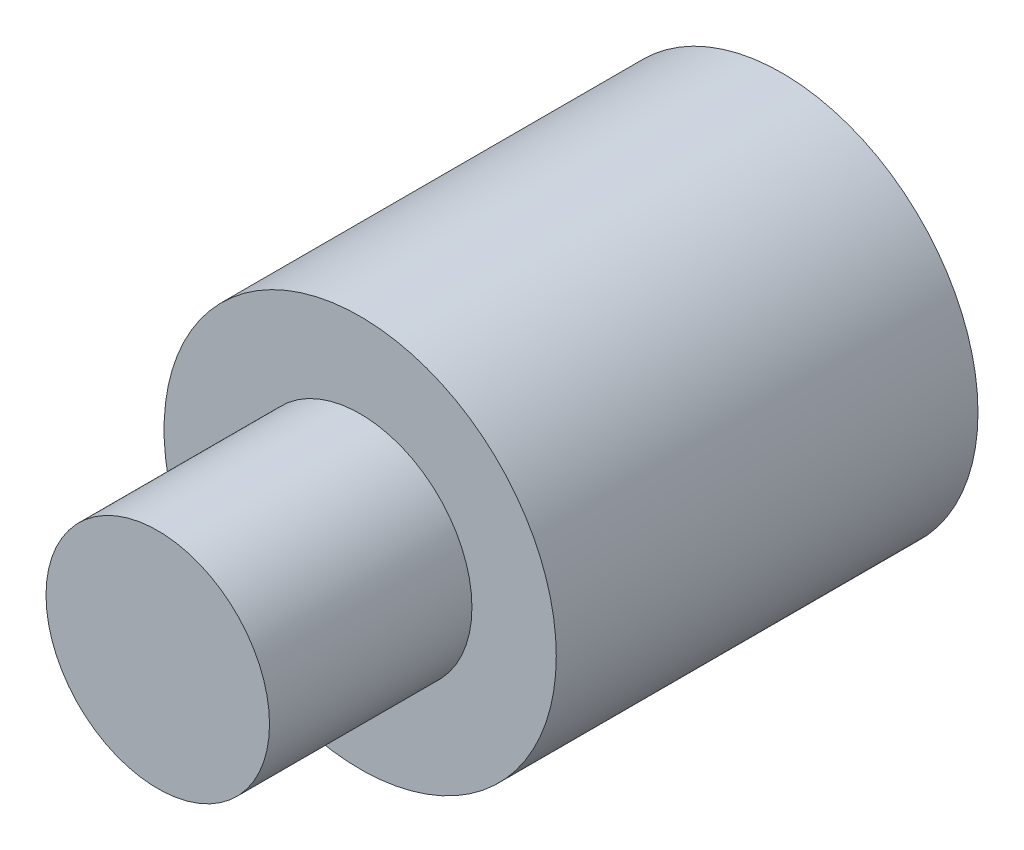
SolidWorks part; units mm, degrees
ref_plane "Front Plane" through (0, 0, 0) normal (0, 0, 1) x (1, 0, 0)
ref_plane "Top Plane" through (0, 0, 0) normal (0, 1, 0) x (1, 0, 0)
ref_plane "Right Plane" through (0, 0, 0) normal (1, 0, 0) x (0, 0, -1)
sketch "Sketch1" plane through (0, 0, 0) normal (0, 0, 1) x (1, 0, 0)
  circle A0 centre (0, 0) radius 4.65
  circle A1 centre (0, 0) radius 2.65
  dimension "D1" = 2
  dimension "D2" = 5.3
extrude "Boss-Extrude1" add sketch "Sketch1" along normal blind 9
sketch "Sketch2" plane through (0, 0, 9) normal (0, 0, 1) x (1, 0, 0)
  circle A0 centre (0, 0) radius 4.65 construction
  circle A1 centre (0, 0) radius 4.65
extrude "Boss-Extrude2" add sketch "Sketch2" along normal blind 1
sketch "Sketch3" plane through (0, 0, 10) normal (0, 0, 1) x (1, 0, 0)
  circle A0 centre (0, 0) radius 2.65
  dimension "D1" = 5.3
extrude "Boss-Extrude3" add sketch "Sketch3" along normal blind 4.8
